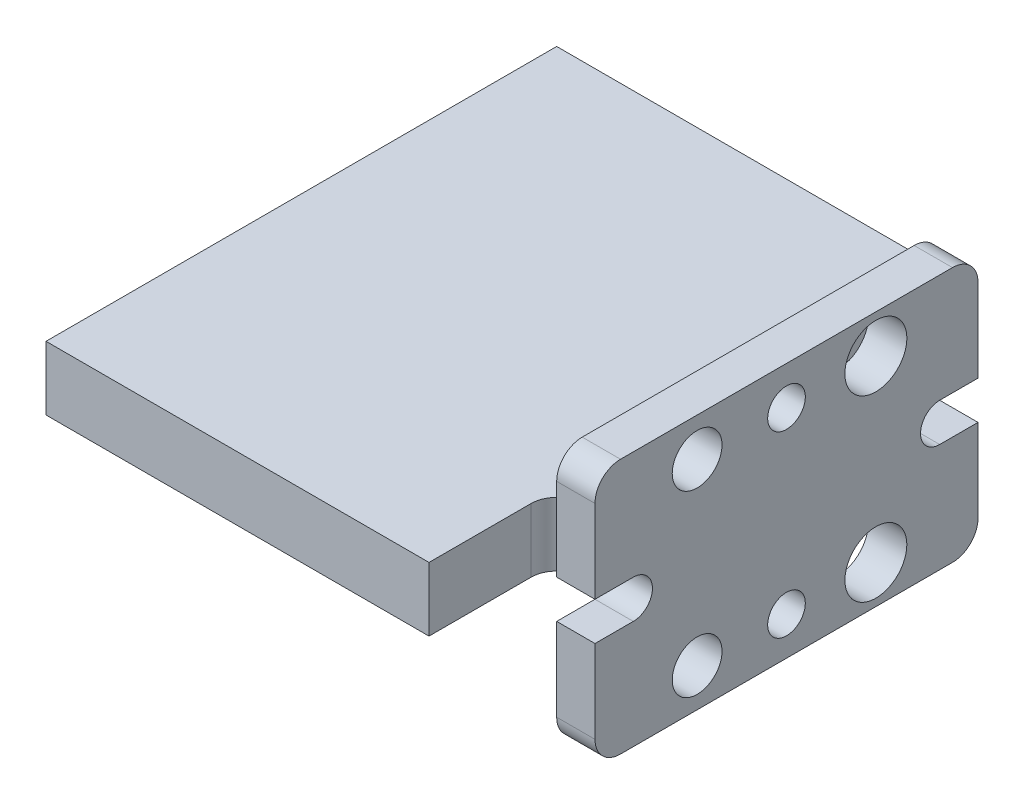
SolidWorks part; units mm, degrees
ref_plane "前视基准面" through (0, 0, 0) normal (0, 0, 1) x (1, 0, 0)
ref_plane "上视基准面" through (0, 0, 0) normal (0, 1, 0) x (1, 0, 0)
ref_plane "右视基准面" through (0, 0, 0) normal (1, 0, 0) x (0, 0, -1)
sketch "草图1" plane through (0, 0, 0) normal (1, 0, 0) x (0, 0, -1)
  line L1 (-10, 2.5) -> (10, 2.5)
  line L2 (-10, 2.5) -> (-10, -2.5)
  line L3 (-10, -2.5) -> (10, -2.5)
  line L4 (10, 2.5) -> (10, -2.5)
  line L5 (-10, 2.5) -> (10, -2.5) construction
  line L6 (-10, -2.5) -> (10, 2.5) construction
  point P0 (0, 0)
  dimension "D1" = 5
  dimension "D2" = 20
extrude "凸台-拉伸1" add sketch "草图1" against normal blind 35
sketch "草图2" plane through (0, 0, 0) normal (1, 0, 0) x (0, 0, -1)
  line L1 (-15, 10) -> (15, 10)
  line L2 (-15, 10) -> (-15, -10)
  line L3 (-15, -10) -> (15, -10)
  line L4 (15, 10) -> (15, -10)
  line L5 (-15, 10) -> (15, -10) construction
  line L6 (-15, -10) -> (15, 10) construction
  point P0 (0, 0)
  dimension "D1" = 20
  dimension "D2" = 30
extrude "凸台-拉伸2" add sketch "草图2" along normal blind 3
fillet "圆角1" radius 2 1 edges at (1.5, 10, -15)
fillet "圆角2" radius 2 1 edges at (1.5, 10, 15)
fillet "圆角3" radius 2 1 edges at (1.5, -10, -15)
fillet "圆角4" radius 2 1 edges at (1.5, -10, 15)
sketch "草图4" plane through (0, 0, 0) normal (0, 1, 0) x (1, 0, 0)
  line L0 (-71.4991, 0) -> (19.3429, 0) construction
  line L1 (-35, 20) -> (-5, 20)
  line L2 (-35, 20) -> (-35, -20)
  line L3 (-35, -20) -> (-5, -20)
  line L4 (-5, 20) -> (-5, -20)
  line L5 (0, 13) -> (0, -13) construction
  point P7 (-35, 0)
  dimension "D1" = 30
  dimension "D2" = 20
  dimension "D3" = 5
extrude "凸台-拉伸3" add sketch "草图4" along normal mid plane 5
fillet "圆角5" radius 2 1 edges at (-5, 0, -10)
fillet "圆角6" radius 2 1 edges at (-5, 0, 10)
sketch "草图5" plane through (0, 0, 0) normal (1, 0, 0) x (0, 0, -1)
  line L0 (-15, 8) -> (-15, -8) construction
  line L1 (-12, -1.5) -> (-15, -1.5)
  line L2 (0, -12.7004) -> (0, 18.7249) construction
  line L3 (-12, 1.5) -> (-15, 1.5)
  line L4 (-15, -1.5) -> (-15, 1.5)
  line L5 (-12, -1.5) -> (-15, 1.5) construction
  line L6 (-12, 1.5) -> (-15, -1.5) construction
  line L7 (-18.2451, 0) -> (18.228, 0) construction
  line L8 (12, 1.5) -> (15, 1.5)
  line L9 (12, -1.5) -> (15, -1.5)
  line L10 (15, -1.5) -> (15, 1.5)
  arc A0 (-12, -1.5) -> (-12, 1.5) centre (-12, 0) ccw
  arc A1 (12, -1.5) -> (12, 1.5) centre (12, 0) cw
  point P0 (-13.5, 0)
  point P8 (-15, 0)
  point P14 (-13.5, 1.5)
  point P19 (13.5, 1.5)
  dimension "D1" = 3
  dimension "D2" = 3
extrude "切除-拉伸2" cut sketch "草图5" along normal blind 3
sketch "草图6" plane through (0, 0, 0) normal (1, 0, 0) x (0, 0, -1)
  line L0 (0, -12.2212) -> (0, 15.5615) construction
  line L1 (-13, -10) -> (13, -10) construction
  line L2 (-7, -12.2212) -> (-7, 15.5615) construction
  line L3 (7, -12.2212) -> (7, 15.5615) construction
  line L5 (23.6468, 0) -> (-26.4286, 0) construction
  line L6 (-17.956, -7) -> (17.956, -7) construction
  circle A0 centre (0, -7) radius 1.475
  circle A1 centre (-7, -7) radius 1.95
  circle A2 centre (7, -7) radius 2.425
  circle A3 centre (7, 7) radius 2.425
  circle A4 centre (0, 7) radius 1.475
  circle A5 centre (-7, 7) radius 1.95
  point P19 (0, 0)
  point P20 (0, 0)
  point P21 (0, 0)
  point P22 (0, 0)
  point P23 (0, 0)
  point P24 (0, 0)
  dimension "D1" = 2.95
  dimension "D4" = 4.85
  dimension "D5" = 3.9
  dimension "D6" = 7
  dimension "D2" = 3
  dimension "D3" = 7
extrude "切除-拉伸3" cut sketch "草图6" along normal blind 3
sketch "草图8" plane through (0, 0, -15) normal (0, 0, -1) x (-1, 0, 0)
  line L0 (0, -8) -> (0, -1.5) construction
  line L1 (0, -2.5) -> (-3, -2.5)
  line L2 (0, -2.5) -> (0, -10)
  line L3 (0, -10) -> (-3, -10)
  line L4 (-3, -2.5) -> (-3, -10)
  line L5 (0, -10) -> (-3, -10) construction
  line L6 (-3, -8) -> (-3, -1.5) construction
  line L7 (3, -2.5) -> (0, -2.5) construction
